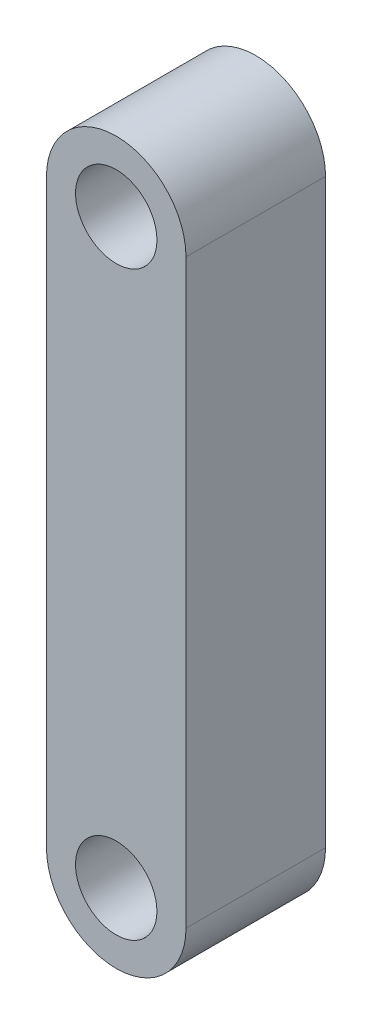
SolidWorks part; units mm, degrees
material "AISI 304"
ref_plane "Front Plane" through (0, 0, 0) normal (0, 0, 1) x (1, 0, 0)
ref_plane "Top Plane" through (0, 0, 0) normal (0, 1, 0) x (1, 0, 0)
ref_plane "Right Plane" through (0, 0, 0) normal (1, 0, 0) x (0, 0, -1)
sketch "Sketch1" plane through (0, 0, 0) normal (0, 0, 1) x (1, 0, 0)
  line L0 (-6, 0) -> (-6, -50)
  line L2 (6, 0) -> (6, -50)
  arc A0 (6, 0) -> (-6, 0) centre (0, 0) ccw
  circle A3 centre (0, 0) radius 3.5
  arc A5 (-6, -50) -> (6, -50) centre (0, -50) ccw
  circle A6 centre (0, -50) radius 3.5
  dimension "D1" = 7
  dimension "D2" = 6
  dimension "D5" = 7
  dimension "D6" = 12
  dimension "D3" = 50
extrude "Boss-Extrude1" add sketch "Sketch1" against normal blind 12
cosmetic thread "Cosmetic Thread1"
cosmetic thread "Cosmetic Thread2"
